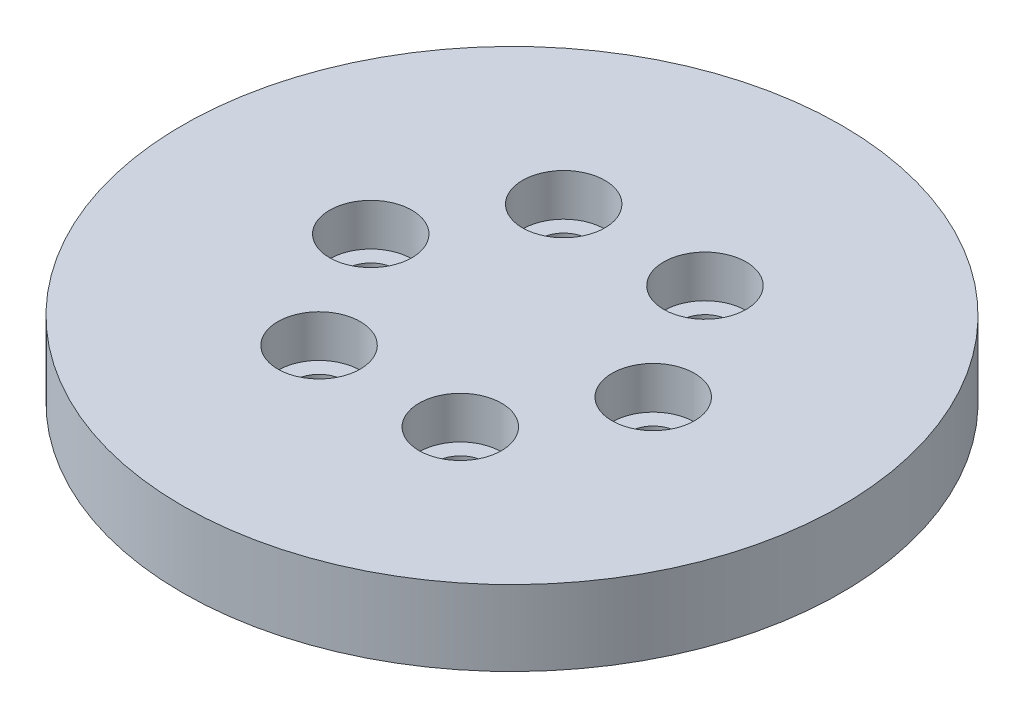
SolidWorks part; units mm, degrees
material "6063-O"
ref_plane "Front Plane" through (0, 0, 0) normal (0, 0, 1) x (1, 0, 0)
ref_plane "Top Plane" through (0, 0, 0) normal (0, 1, 0) x (1, 0, 0)
ref_plane "Right Plane" through (0, 0, 0) normal (1, 0, 0) x (0, 0, -1)
sketch "Sketch1" plane through (0, 0, 0) normal (0, 1, 0) x (1, 0, 0)
  circle A0 centre (0, 0) radius 22.225
  dimension "D1" = 44.45
extrude "Boss-Extrude1" add sketch "Sketch1" along normal blind 5.08
sketch "Sketch2" plane through (0, 5.08, 0) normal (0, 1, 0) x (1, 0, 0)
  line L0 (0, 0) -> (-9.525, 0) construction
  circle A0 centre (0, 0) radius 9.525 construction
  circle A1 centre (-9.525, 0) radius 1.5875
  circle A2 centre (-4.7625, 8.2489) radius 1.5875
  circle A3 centre (4.7625, 8.2489) radius 1.5875
  circle A4 centre (9.525, 0) radius 1.5875
  circle A5 centre (4.7625, -8.2489) radius 1.5875
  circle A6 centre (-4.7625, -8.2489) radius 1.5875
  point P6 (-4.7633, -8.2484)
  point P7 (4.7488, -8.2568)
  point P17 (0, 0)
  dimension "D1" = 19.05
  dimension "D2" = 3.175
  dimension "D3" = 6
hole_wizard "CBORE for #4 Socket Head Cap Screw1" positions "Sketch3" profile "Sketch4" counterbore size "#4" standard "ANSI Inch" end condition through all
sketch "Sketch3" plane through (0, 5.08, 0) normal (0, 1, 0) x (1, 0, 0)
  point P0 (-9.525, 0)
  point P3 (-4.7625, 8.2489)
  point P6 (4.7625, 8.2489)
  point P9 (9.525, 0)
  point P12 (4.7625, -8.2489)
  point P15 (-4.7625, -8.2489)
sketch "Sketch4" plane through (-9.525, 5.08, 0) normal (1, 0, 0) x (0, 0, 1)
  line L0 (0, 0) -> (0, 5.08)
  line L1 (0, 5.08) -> (1.6319, 5.08)
  line L3 (1.6319, 5.08) -> (1.632, 2.8448)
  line L4 (1.632, 2.8448) -> (2.7788, 2.8448)
  line L5 (2.7788, 2.8448) -> (2.7788, 0)
  line L7 (2.7788, 0) -> (0, 0)
  line L11 (0, -6.35) -> (0, 107.95) construction
  dimension "Thru Hole Dia." = 3.2639
  dimension "Thru Hole Depth" = 5.08
  dimension "C'Bore Dia." = 5.5575
  dimension "C'Bore Depth" = 2.8448
